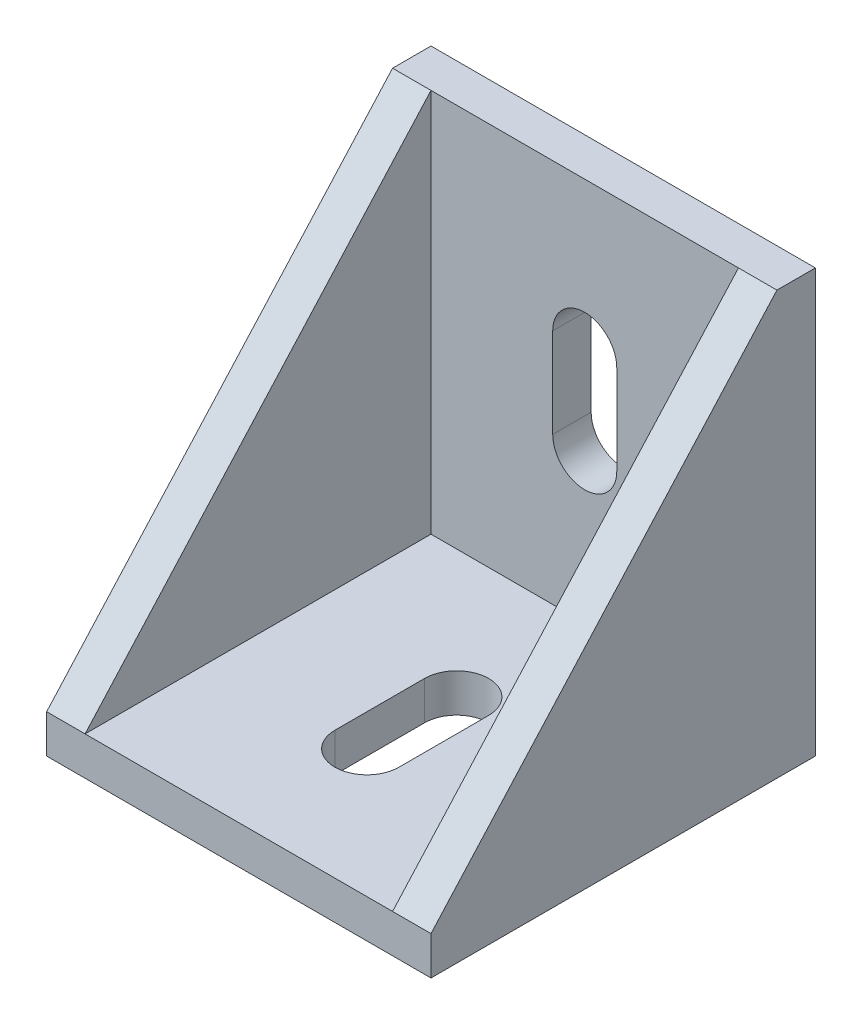
SolidWorks part; units mm, degrees
material "1060 Alloy"
ref_plane "Front Plane" through (0, 0, 0) normal (0, 0, 1) x (1, 0, 0)
ref_plane "Top Plane" through (0, 0, 0) normal (0, 1, 0) x (1, 0, 0)
ref_plane "Right Plane" through (0, 0, 0) normal (1, 0, 0) x (0, 0, -1)
sketch "Sketch1" plane through (0, 0, 0) normal (0, 1, 0) x (1, 0, 0)
  line L0 (0, 0) -> (30, 0)
  line L1 (30, 0) -> (30, -30)
  line L2 (30, -30) -> (0, -30)
  line L3 (0, -30) -> (0, 0)
  dimension "D1" = 30
  dimension "D2" = 30
extrude "Boss-Extrude1" add sketch "Sketch1" along normal blind 3
sketch "Sketch2" plane through (0, 0, 0) normal (0, 0, -1) x (-1, 0, 0)
  line L0 (-30, 3) -> (-30, 33)
  line L1 (-30, 33) -> (0, 33)
  line L2 (0, 33) -> (0, 3)
  line L3 (-30, 3) -> (0, 3) construction
  line L4 (0, 3) -> (-30, 3)
  dimension "D1" = 30
extrude "Boss-Extrude2" add sketch "Sketch2" against normal blind 3
sketch "Sketch3" plane through (0, 0, 0) normal (-1, 0, 0) x (0, 0, 1)
  line L1 (3, 33) -> (3, 3)
  line L2 (3, 3) -> (30, 3)
  line L4 (3, 33) -> (30, 3)
extrude "Boss-Extrude3" add sketch "Sketch3" against normal blind 3
sketch "Sketch4" plane through (30, 0, 0) normal (1, 0, 0) x (0, 0, -1)
  line L2 (-30, 3) -> (-3, 3)
  line L3 (-3, 3) -> (-3, 33)
  line L5 (-3, 33) -> (-30, 3)
extrude "Boss-Extrude4" add sketch "Sketch4" against normal blind 3
sketch "Sketch5" plane through (0, 0, 3) normal (0, 0, 1) x (1, 0, 0)
  line L0 (15, 33) -> (15, 3) construction
  line L1 (3, 33) -> (27, 33) construction
  line L2 (27, 3) -> (3, 3) construction
  line L3 (3, 18) -> (27, 18) construction
  line L4 (3, 33) -> (3, 3) construction
  line L5 (27, 3) -> (27, 33) construction
  line L6 (15, 14.5) -> (15, 21.5) construction
  line L7 (12.5, 14.5) -> (12.5, 21.5)
  line L8 (17.5, 14.5) -> (17.5, 21.5)
  arc A0 (12.5, 14.5) -> (17.5, 14.5) centre (15, 14.5) ccw
  arc A1 (17.5, 21.5) -> (12.5, 21.5) centre (15, 21.5) ccw
  point P14 (15, 18)
extrude "Cut-Extrude1" cut sketch "Sketch5" against normal blind 3
sketch "Sketch6" plane through (0, 3, 0) normal (0, 1, 0) x (1, 0, 0)
  line L0 (3, -16.5) -> (27, -16.5) construction
  line L3 (3, -3) -> (3, -30) construction
  line L6 (27, -30) -> (27, -3) construction
  line L7 (15, -3) -> (15, -30) construction
  line L8 (27, -3) -> (3, -3) construction
  line L9 (3, -30) -> (27, -30) construction
  line L10 (15, -20) -> (15, -13) construction
  line L12 (12.5, -20) -> (12.5, -13)
  line L13 (17.5, -20) -> (17.5, -13)
  arc A0 (12.5, -20) -> (17.5, -20) centre (15, -20) ccw
  arc A1 (17.5, -13) -> (12.5, -13) centre (15, -13) ccw
  point P16 (15, -16.5)
  dimension "D1" = 7
extrude "Cut-Extrude2" cut sketch "Sketch6" against normal blind 3
